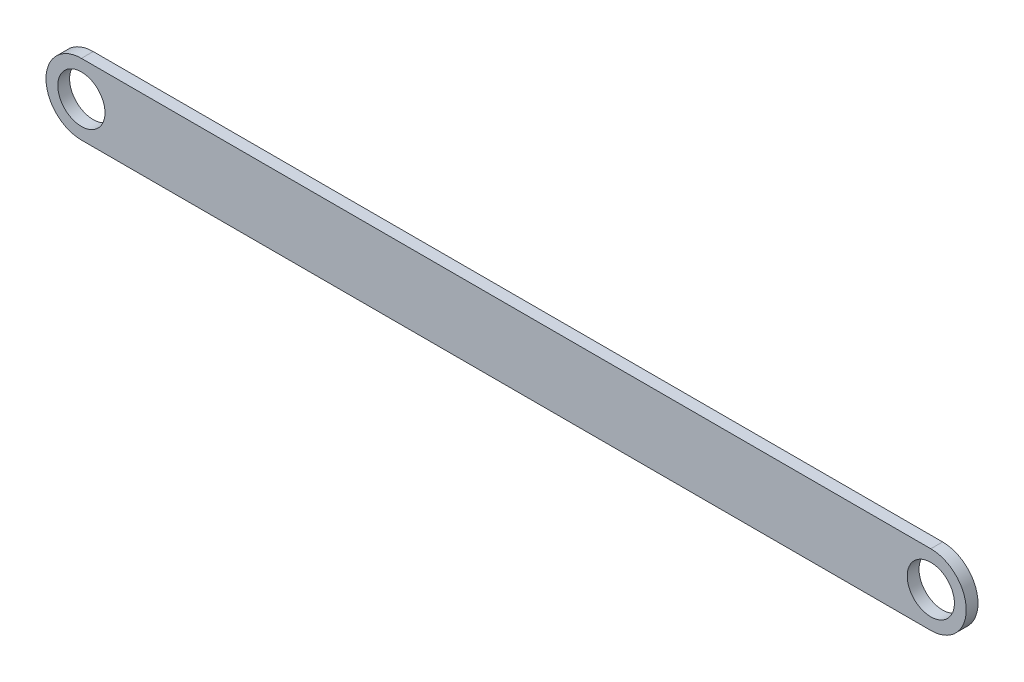
SolidWorks part; units mm, degrees
ref_plane "Alzado" through (0, 0, 0) normal (0, 0, 1) x (1, 0, 0)
ref_plane "Planta" through (0, 0, 0) normal (0, 1, 0) x (1, 0, 0)
ref_plane "Vista lateral" through (0, 0, 0) normal (1, 0, 0) x (0, 0, -1)
sketch "Croquis2" plane through (0, 0, 0) normal (0, 0, 1) x (1, 0, 0)
  line L0 (-90, 0) -> (90, 0) construction
  line L1 (-90, 7.5) -> (90, 7.5)
  line L2 (-90, -7.5) -> (90, -7.5)
  arc A0 (-90, 7.5) -> (-90, -7.5) centre (-90, 0) ccw
  arc A1 (90, -7.5) -> (90, 7.5) centre (90, 0) ccw
  point P2 (0, 0)
  dimension "D1" = 180
extrude "Saliente-Extruir1" add sketch "Croquis2" along normal blind 2.5
sketch "Croquis3" plane through (0, 0, 2.5) normal (0, 0, 1) x (1, 0, 0)
  circle A0 centre (-90, 0) radius 5
  circle A1 centre (90, 0) radius 5
extrude "Cortar-Extruir1" cut sketch "Croquis3" against normal through all
